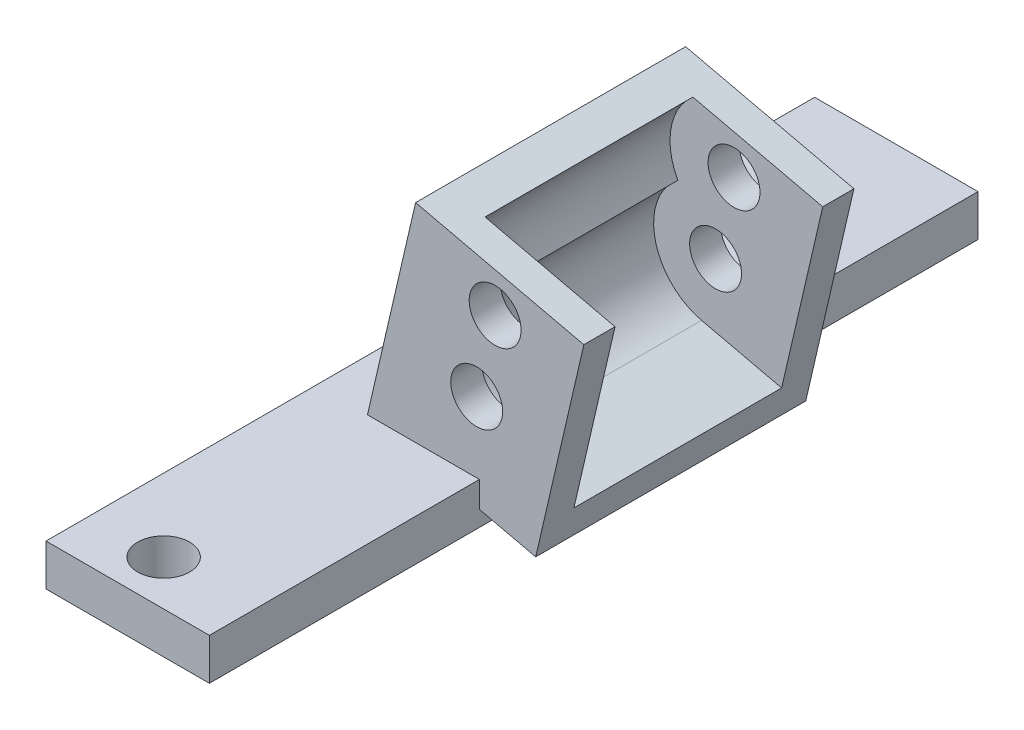
SolidWorks part; units mm, degrees
ref_plane "Front Plane" through (0, 0, 0) normal (0, 0, 1) x (1, 0, 0)
ref_plane "Top Plane" through (0, 0, 0) normal (0, 1, 0) x (1, 0, 0)
ref_plane "Right Plane" through (0, 0, 0) normal (1, 0, 0) x (0, 0, -1)
sketch "Sketch1" plane through (0, 0, 0) normal (0, 0, 1) x (1, 0, 0)
  line L0 (-342.9068, 232.3174) -> (-348.7913, 206.904)
  line L1 (-327.0245, 228.6398) -> (-358.7891, 235.995) construction
  line L2 (-348.7913, 206.904) -> (-369.3615, 211.6671)
  line L3 (-369.3615, 211.6671) -> (-363.477, 237.0805)
  line L4 (-363.477, 237.0805) -> (-342.9068, 232.3174)
  line L5 (-338.6024, 208.4556) -> (-357.7178, 212.8818) construction
  line L6 (-338.6024, 208.4556) -> (-357.7178, 212.8818)
  arc A0 (-358.7891, 235.995) -> (-360.6297, 226.2561) centre (-353.7541, 230) ccw construction
  arc A1 (-360.6297, 226.2561) -> (-362.9827, 217.3077) centre (-356.0099, 220.2578) ccw construction
  arc A2 (-362.9827, 217.3077) -> (-357.7178, 212.8818) centre (-356.0099, 220.2578) ccw construction
  arc A3 (-358.7891, 235.995) -> (-360.6297, 226.2561) centre (-353.7541, 230) ccw
  arc A4 (-360.6297, 226.2561) -> (-362.9827, 217.3077) centre (-356.0099, 220.2578) ccw
  arc A5 (-362.9827, 217.3077) -> (-357.7178, 212.8818) centre (-356.0099, 220.2578) ccw
  dimension "D1" = 3.81
  dimension "D2" = 6.35
extrude "Boss-Extrude1" add sketch "Sketch1" against normal up to surface (25.4 mm away) contours A5 A4 A3 L4 L3 L2 L0 L6
sketch "Sketch2" plane through (0, 0, -25.4) normal (0, 0, -1) x (-1, 0, 0)
  line L0 (347.9318, 210.6158) -> (342.9068, 232.3174)
  line L1 (337.0113, 230.9523) -> (358.7891, 235.995) construction
  line L2 (342.9068, 232.3174) -> (358.7891, 235.995)
  line L3 (347.9318, 210.6158) -> (357.7178, 212.8818)
  arc A0 (358.7891, 235.995) -> (360.6297, 226.2561) centre (353.7541, 230) cw
  arc A1 (360.6297, 226.2561) -> (357.7178, 212.8818) centre (356.0099, 220.2578) cw
  circle A2 centre (356.0099, 220.2578) radius 3.175 construction
  circle A3 centre (353.7541, 230) radius 3.175 construction
  circle A4 centre (356.0099, 220.2578) radius 3.175
  circle A5 centre (353.7541, 230) radius 3.175
  circle A6 centre (353.7541, 230) radius 3.175
  circle A7 centre (356.0099, 220.2578) radius 3.175
  line M7 (357.7178, 212.8818) -> (347.9318, 210.6158)
  line M8 (347.9318, 210.6158) -> (348.7913, 206.904)
  line M9 (348.7913, 206.904) -> (369.3615, 211.6671)
  line M10 (369.3615, 211.6671) -> (363.477, 237.0805)
  line M11 (363.477, 237.0805) -> (358.7891, 235.995)
  arc M12 (358.7891, 235.995) -> (360.6297, 226.2561) centre (353.7541, 230) cw
  arc M13 (360.6297, 226.2561) -> (357.7178, 212.8818) centre (356.0099, 220.2578) cw
extrude "Boss-Extrude3" add sketch "Sketch2" along normal blind 3.81 contours L2 L0 A5 A4 M7 M13 M12 | M13 M7 M8 M9 M10 M11 M12
sketch "Sketch3" plane through (0, 0, 0) normal (0, 0, 1) x (1, 0, 0)
  line L0 (-358.7891, 235.995) -> (-342.9068, 232.3174)
  line L1 (-342.9068, 232.3174) -> (-348.7913, 206.904)
  line L2 (-348.7913, 206.904) -> (-369.3615, 211.6671)
  line L3 (-369.3615, 211.6671) -> (-363.477, 237.0805)
  circle A0 centre (-356.0099, 220.2578) radius 3.175 construction
  circle A1 centre (-353.7541, 230) radius 3.175 construction
  circle A2 centre (-356.0099, 220.2578) radius 3.175
  circle A3 centre (-353.7541, 230) radius 3.175
  arc M3 (-357.7178, 212.8818) -> (-360.6297, 226.2561) centre (-356.0099, 220.2578) cw
  arc M4 (-360.6297, 226.2561) -> (-358.7891, 235.995) centre (-353.7541, 230) cw
  line M5 (-358.7891, 235.995) -> (-363.477, 237.0805)
  line M6 (-363.477, 237.0805) -> (-369.3615, 211.6671)
  line M7 (-369.3615, 211.6671) -> (-348.7913, 206.904)
  line M8 (-348.7913, 206.904) -> (-347.9318, 210.6158)
  line M9 (-347.9318, 210.6158) -> (-357.7178, 212.8818)
extrude "Boss-Extrude4" add sketch "Sketch3" along normal blind 3.81 contours L1 L0 A3 A2 M4 M3 M9 | M9 M3 M4 M5 M6 M7 M8
ref_plane "Plane2" through (0, 211.6671, 0) normal (0, 1, 0) x (1, 0, 0)
sketch "Sketch4" plane through (0, 211.6671, 0) normal (0, 1, 0) x (1, 0, 0)
  line L1 (-375.6488, 57.15) -> (-355.6726, 57.15)
  line L2 (-375.6488, 57.15) -> (-375.6488, -36.83)
  line L3 (-375.6488, -36.83) -> (-355.6726, -36.83)
  line L4 (-355.6726, 57.15) -> (-355.6726, -36.83)
  dimension "D1" = 33.02
  dimension "D2" = 27.94
extrude "Boss-Extrude5" add sketch "Sketch4" against normal blind 5.08
sketch "Sketch5" plane through (0, 211.6671, 0) normal (0, 1, 0) x (1, 0, 0)
  line L0 (-375.6488, 57.15) -> (-375.6488, -36.83) construction
  circle A0 centre (-366.7588, 43.9091) radius 3.175
  circle A1 centre (-366.7588, -31.3319) radius 3.175
  dimension "D1" = 8.89
  dimension "D2" = 8.89
extrude "Cut-Extrude1" cut sketch "Sketch5" along normal blind 5.08 and the other way through all
